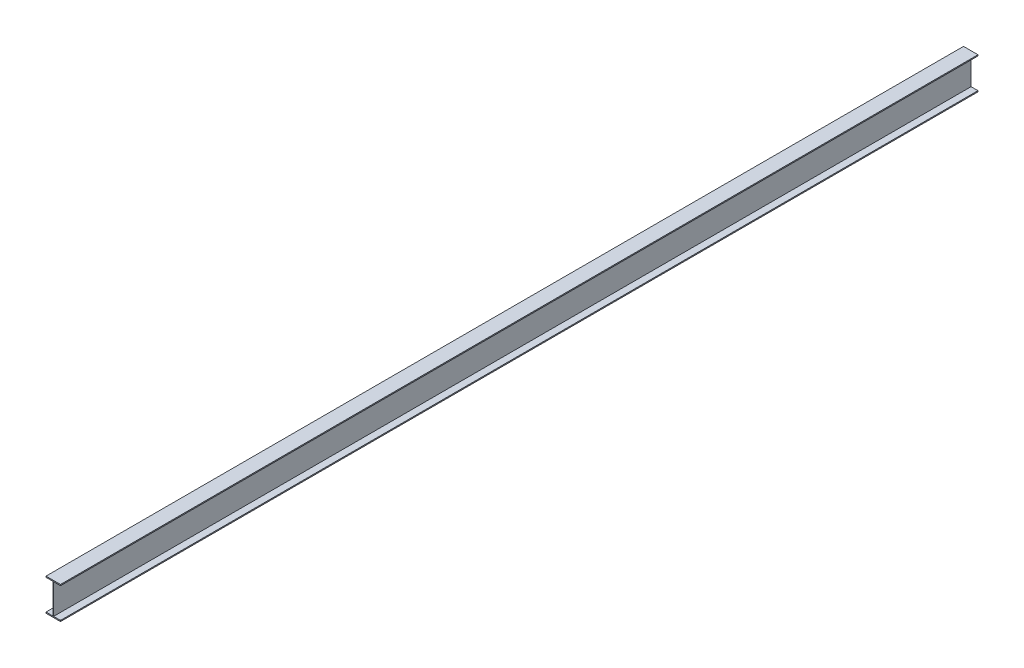
SolidWorks part; units mm, degrees
ref_plane "Front Plane" through (0, 0, 0) normal (0, 0, 1) x (1, 0, 0)
ref_plane "Top Plane" through (0, 0, 0) normal (0, 1, 0) x (1, 0, 0)
ref_plane "Right Plane" through (0, 0, 0) normal (1, 0, 0) x (0, 0, -1)
sketch "Sketch1" plane through (0, 0, 0) normal (0, 0, 1) x (1, 0, 0)
  line L0 (-72.5249, -243.4737) -> (107.4751, -243.4737)
  line L1 (107.4751, -243.4737) -> (107.4751, -229.9737)
  line L2 (107.4751, -229.9737) -> (21.7751, -229.9737)
  line L3 (-72.5249, 156.5263) -> (107.4751, 156.5263)
  line L4 (107.4751, 156.5263) -> (107.4751, 143.0263)
  line L5 (107.4751, 143.0263) -> (21.7751, 143.0263)
  line L6 (21.7751, -229.9737) -> (21.7751, 143.0263)
  line L7 (-72.5249, 156.5263) -> (-72.5249, 143.0263)
  line L8 (-72.5249, 143.0263) -> (13.1751, 143.0263)
  line L9 (-72.5249, -243.4737) -> (-72.5249, -229.9737)
  line L10 (-72.5249, -229.9737) -> (13.1751, -229.9737)
  line L11 (13.1751, -229.9737) -> (13.1751, 143.0263)
extrude "Boss-Extrude1" add sketch "Sketch1" along normal blind 11400
